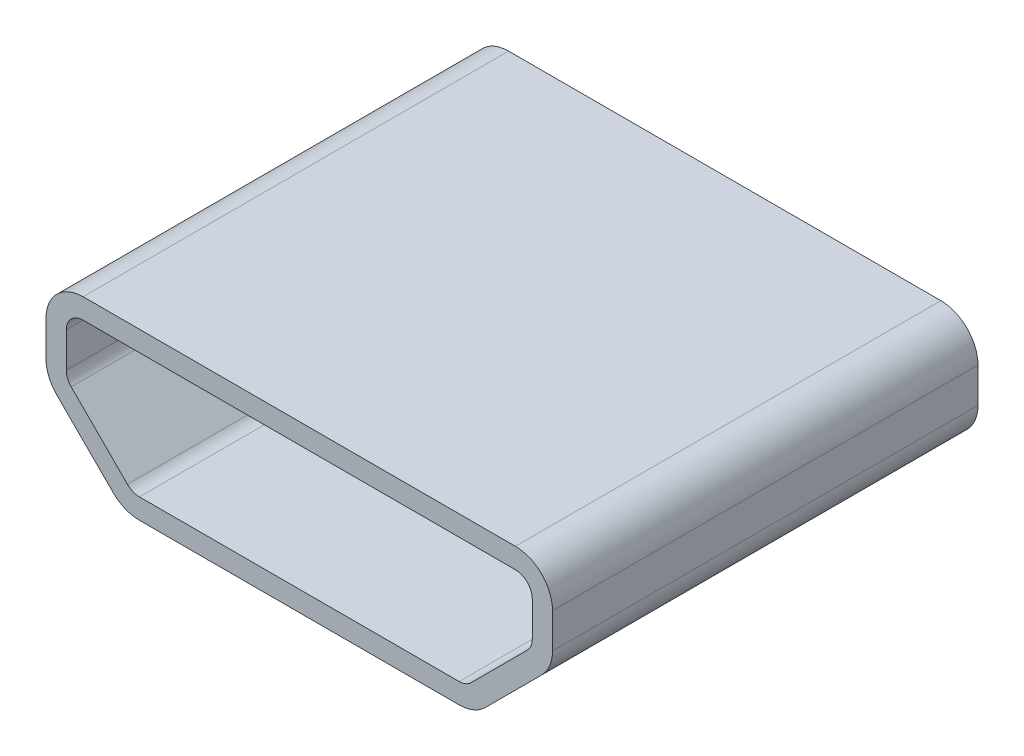
SolidWorks part; units mm, degrees
ref_plane "Plano frontal" through (0, 0, 0) normal (0, 0, 1) x (1, 0, 0)
ref_plane "Plano superior" through (0, 0, 0) normal (0, 1, 0) x (1, 0, 0)
ref_plane "Plano direito" through (0, 0, 0) normal (1, 0, 0) x (0, 0, -1)
sketch "Esboço1" plane through (0, 0, 0) normal (0, 0, 1) x (1, 0, 0)
  line L5 (0, 0) -> (0, 1.225) construction
  line L6 (0, 0) -> (1.3965, 0) construction
  line L7 (3.2, 1.225) -> (-3.2, 1.225)
  line L9 (-3.75, 0.675) -> (-3.75, 0.1578)
  line L10 (-2.3672, -1.225) -> (2.3672, -1.225)
  line L11 (-2.7561, -1.0639) -> (-3.5889, -0.2311)
  line L12 (2.7561, -1.0639) -> (3.5889, -0.2311)
  line L13 (3.75, 0.675) -> (3.75, 0.1578)
  arc A2 (-3.2, 1.225) -> (-3.75, 0.675) centre (-3.2, 0.675) ccw
  arc A3 (-2.3672, -1.225) -> (-2.7561, -1.0639) centre (-2.3672, -0.675) cw
  arc A4 (-3.5889, -0.2311) -> (-3.75, 0.1578) centre (-3.2, 0.1578) cw
  arc A5 (3.5889, -0.2311) -> (3.75, 0.1578) centre (3.2, 0.1578) ccw
  arc A6 (2.3672, -1.225) -> (2.7561, -1.0639) centre (2.3672, -0.675) ccw
  arc A7 (3.2, 1.225) -> (3.75, 0.675) centre (3.2, 0.675) cw
  point P8 (2.595, -1.225)
  point P12 (-2.595, -1.225)
  point P25 (0, -1.225)
  dimension "D5" = 0.55
  dimension "D6" = 0.55
  dimension "D1" = 2.45
  dimension "D2" = 3.75
  dimension "D3" = 45
  dimension "D4" = 2.595
extrude "Ressalto-extrusão1" add sketch "Esboço1" along normal mid plane 6.3
sketch "Esboço2" plane through (0, 0, 3.15) normal (0, 0, 1) x (1, 0, 0)
  line L0 (2.7561, -1.0639) -> (3.5889, -0.2311) construction
  line L1 (3.75, 0.1578) -> (3.75, 0.675) construction
  line L2 (3.2, 1.225) -> (-3.2, 1.225) construction
  line L3 (-2.3672, -1.225) -> (2.3672, -1.225) construction
  line L4 (-3.5889, -0.2311) -> (-2.7561, -1.0639) construction
  line L5 (-3.75, 0.675) -> (-3.75, 0.1578) construction
  line L6 (2.7561, -1.0639) -> (3.5889, -0.2311)
  line L7 (3.75, 0.1578) -> (3.75, 0.675)
  line L8 (3.2, 1.225) -> (-3.2, 1.225)
  line L9 (-2.3672, -1.225) -> (2.3672, -1.225)
  line L10 (-3.5889, -0.2311) -> (-2.7561, -1.0639)
  line L11 (-3.75, 0.675) -> (-3.75, 0.1578)
  line L12 (-3.45, 0.675) -> (-3.45, 0.1578)
  line L13 (-3.3768, -0.019) -> (-2.544, -0.8518)
  line L14 (-2.3672, -0.925) -> (2.3672, -0.925)
  line L15 (2.544, -0.8518) -> (3.3768, -0.019)
  line L16 (3.45, 0.1578) -> (3.45, 0.675)
  line L17 (3.2, 0.925) -> (-3.2, 0.925)
  arc A0 (2.3672, -1.225) -> (2.7561, -1.0639) centre (2.3672, -0.675) ccw construction
  arc A1 (3.5889, -0.2311) -> (3.75, 0.1578) centre (3.2, 0.1578) ccw construction
  arc A2 (3.75, 0.675) -> (3.2, 1.225) centre (3.2, 0.675) ccw construction
  arc A3 (-2.7561, -1.0639) -> (-2.3672, -1.225) centre (-2.3672, -0.675) ccw construction
  arc A4 (-3.75, 0.1578) -> (-3.5889, -0.2311) centre (-3.2, 0.1578) ccw construction
  arc A5 (-3.2, 1.225) -> (-3.75, 0.675) centre (-3.2, 0.675) ccw construction
  arc A6 (2.3672, -1.225) -> (2.7561, -1.0639) centre (2.3672, -0.675) ccw
  arc A7 (3.5889, -0.2311) -> (3.75, 0.1578) centre (3.2, 0.1578) ccw
  arc A8 (3.75, 0.675) -> (3.2, 1.225) centre (3.2, 0.675) ccw
  arc A9 (-2.7561, -1.0639) -> (-2.3672, -1.225) centre (-2.3672, -0.675) ccw
  arc A10 (-3.75, 0.1578) -> (-3.5889, -0.2311) centre (-3.2, 0.1578) ccw
  arc A11 (-3.2, 1.225) -> (-3.75, 0.675) centre (-3.2, 0.675) ccw
  arc A12 (-3.2, 0.925) -> (-3.45, 0.675) centre (-3.2, 0.675) ccw
  arc A13 (-3.45, 0.1578) -> (-3.3768, -0.019) centre (-3.2, 0.1578) ccw
  arc A14 (-2.544, -0.8518) -> (-2.3672, -0.925) centre (-2.3672, -0.675) ccw
  arc A15 (2.3672, -0.925) -> (2.544, -0.8518) centre (2.3672, -0.675) ccw
  arc A16 (3.3768, -0.019) -> (3.45, 0.1578) centre (3.2, 0.1578) ccw
  arc A17 (3.45, 0.675) -> (3.2, 0.925) centre (3.2, 0.675) ccw
  dimension "D1" = 0.3
extrude "Corte-extrusão1" cut sketch "Esboço2" against normal blind 3.5 flip side to cut
